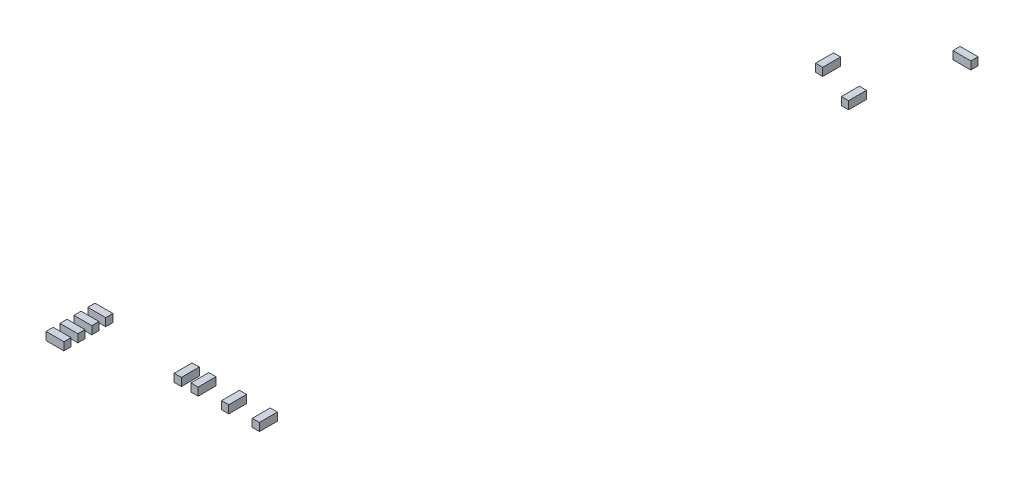
SolidWorks part; units mm, degrees
ref_plane "Front Plane" through (0, 0, 0) normal (0, 0, 1) x (1, 0, 0)
ref_plane "Top Plane" through (0, 0, 0) normal (0, 1, 0) x (1, 0, 0)
ref_plane "Right Plane" through (0, 0, 0) normal (1, 0, 0) x (0, 0, -1)
sketch "Sketch1" plane through (0, 0, 0) normal (0, 1, 0) x (1, 0, 0)
  line L0 (1.143, 0.4572) -> (1.143, 0.889) construction
  line L1 (0, 0.4572) -> (1.143, 0.4572)
  line L2 (0, 0.4572) -> (0, 0)
  line L3 (0, 0) -> (1.143, 0)
  line L4 (1.143, 0.4572) -> (1.143, 0)
  line L5 (0, 1.3462) -> (1.143, 1.3462)
  line L6 (0, 1.3462) -> (0, 0.889)
  line L7 (0, 0.889) -> (1.143, 0.889)
  line L8 (1.143, 1.3462) -> (1.143, 0.889)
  line L9 (0, 2.2352) -> (1.143, 2.2352)
  line L10 (0, 2.2352) -> (0, 1.778)
  line L11 (0, 1.778) -> (1.143, 1.778)
  line L12 (1.143, 2.2352) -> (1.143, 1.778)
  line L13 (0, 3.1242) -> (1.143, 3.1242)
  line L14 (0, 3.1242) -> (0, 2.667)
  line L15 (0, 2.667) -> (1.143, 2.667)
  line L16 (1.143, 3.1242) -> (1.143, 2.667)
  line L17 (1.143, 1.3462) -> (1.143, 1.778) construction
  line L18 (1.143, 2.2352) -> (1.143, 2.667) construction
  line L19 (0, 0) -> (6.858, 0) construction
  line L20 (1.143, 1.778) -> (6.858, 1.778) construction
  line L21 (6.858, 1.778) -> (6.858, 0) construction
  line L23 (6.858, 1.778) -> (6.4008, 1.778)
  line L24 (6.858, 1.778) -> (6.858, 2.921)
  line L25 (6.858, 2.921) -> (6.4008, 2.921)
  line L26 (6.4008, 1.778) -> (6.4008, 2.921)
  line L27 (7.4676, 1.778) -> (7.9248, 1.778)
  line L28 (7.4676, 1.778) -> (7.4676, 2.921)
  line L29 (7.4676, 2.921) -> (7.9248, 2.921)
  line L30 (7.9248, 1.778) -> (7.9248, 2.921)
  line L31 (9.4234, 1.778) -> (9.8806, 1.778)
  line L32 (9.4234, 1.778) -> (9.4234, 2.921)
  line L33 (9.4234, 2.921) -> (9.8806, 2.921)
  line L34 (9.8806, 1.778) -> (9.8806, 2.921)
  line L35 (11.3792, 1.778) -> (11.8364, 1.778)
  line L36 (11.3792, 1.778) -> (11.3792, 2.921)
  line L37 (11.3792, 2.921) -> (11.8364, 2.921)
  line L38 (11.8364, 1.778) -> (11.8364, 2.921)
  line L39 (-3.0988, -0.254) -> (17.2212, -0.254) construction
  line L40 (-3.0988, -0.254) -> (-3.0988, 50.546) construction
  line L41 (-3.0988, 50.546) -> (17.2212, 50.546) construction
  line L42 (17.2212, -0.254) -> (17.2212, 50.546) construction
  line L43 (9.7282, 40.513) -> (10.1854, 40.513)
  line L44 (9.7282, 40.513) -> (9.7282, 39.37)
  line L45 (9.7282, 39.37) -> (10.1854, 39.37)
  line L46 (10.1854, 40.513) -> (10.1854, 39.37)
  line L47 (12.3952, 39.497) -> (12.8524, 39.497)
  line L48 (12.3952, 39.497) -> (12.3952, 38.354)
  line L49 (12.3952, 38.354) -> (12.8524, 38.354)
  line L50 (12.8524, 39.497) -> (12.8524, 38.354)
  line L51 (13.4112, 44.9072) -> (14.5542, 44.9072)
  line L52 (13.4112, 44.9072) -> (13.4112, 44.45)
  line L53 (13.4112, 44.45) -> (14.5542, 44.45)
  line L54 (14.5542, 44.9072) -> (14.5542, 44.45)
  dimension "D1" = 0.4572
  dimension "D2" = 1.3462
  dimension "D3" = 1.143
  dimension "D4" = 6.858
  dimension "D5" = 1.524
  dimension "D6" = 2.413
  dimension "D7" = 2.413
  dimension "D8" = 3.0988
  dimension "D9" = 0.508
  dimension "D10" = 20.32
  dimension "D11" = 50.8
  dimension "D12" = 4.826
  dimension "D13" = 7.493
  dimension "D14" = 39.751
  dimension "D15" = 40.767
  dimension "D16" = 3.81
  dimension "D17" = 4.953
extrude "Boss-Extrude1" add sketch "Sketch1" along normal blind 0.508
